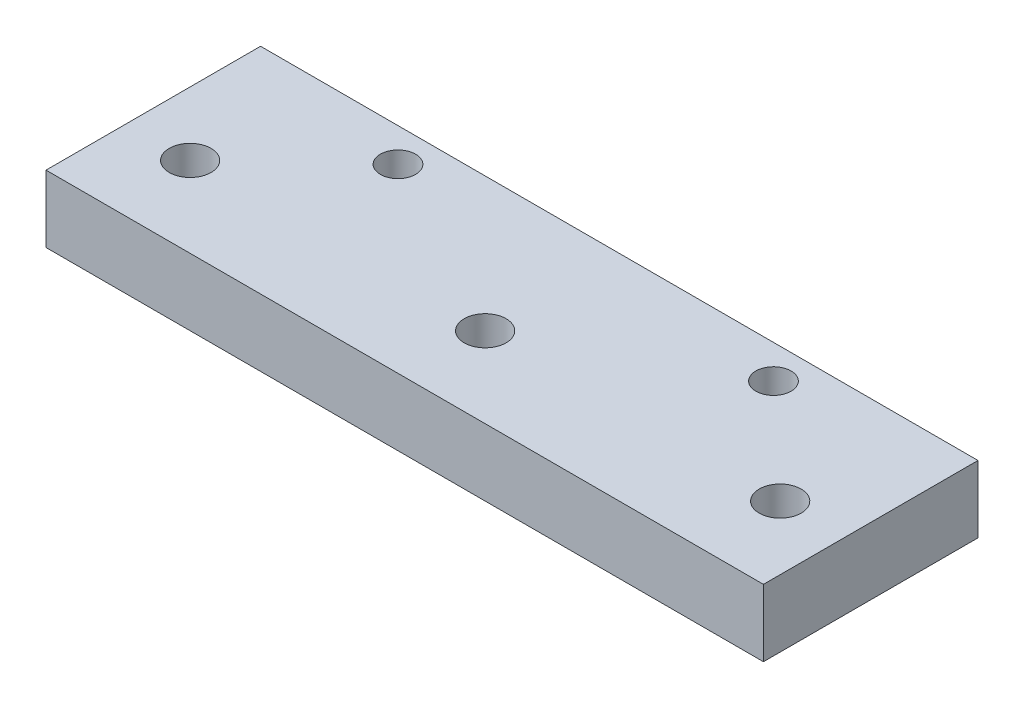
SolidWorks part; units mm, degrees
ref_plane "Front Plane" through (0, 0, 0) normal (0, 0, 1) x (1, 0, 0)
ref_plane "Top Plane" through (0, 0, 0) normal (0, 1, 0) x (1, 0, 0)
ref_plane "Right Plane" through (0, 0, 0) normal (1, 0, 0) x (0, 0, -1)
sketch "Sketch1" plane through (0, 0, 0) normal (0, 1, 0) x (1, 0, 0)
  line L1 (-169.8625, -50.8) -> (169.8625, -50.8)
  line L2 (-169.8625, -50.8) -> (-169.8625, 50.8)
  line L3 (-169.8625, 50.8) -> (169.8625, 50.8)
  line L4 (169.8625, -50.8) -> (169.8625, 50.8)
  line L5 (-169.8625, -50.8) -> (169.8625, 50.8) construction
  line L6 (-169.8625, 50.8) -> (169.8625, -50.8) construction
  point P0 (0, 0)
  dimension "D1" = 169.8625
  dimension "D2" = 50.8
extrude "Boss-Extrude1" add sketch "Sketch1" along normal mid plane 31.75
sketch "Sketch2" plane through (0, 0, 0) normal (0, 1, 0) x (1, 0, 0)
  circle A0 centre (-139.7127, -12.7) radius 9.9187
  circle A1 centre (-0.0127, -12.7) radius 9.9187
  circle A2 centre (139.6873, -12.7) radius 9.9187
  point P6 (0, 0)
  dimension "D1" = 19.8374
  dimension "D2" = 19.8374
  dimension "D3" = 19.8374
  dimension "D4" = 139.7
  dimension "D5" = 279.4
  dimension "D6" = 139.6873
  dimension "D7" = 12.7
extrude "Cut-Extrude2" cut sketch "Sketch2" along normal blind 63.5 from offset 15.875
sketch "Sketch3" plane through (0, 0, 0) normal (0, 1, 0) x (1, 0, 0)
  circle A0 centre (-139.7127, -12.7) radius 15.0876
  circle A1 centre (-0.0127, -12.7) radius 15.0876
  circle A2 centre (139.6873, -12.7) radius 15.0876
  point P6 (0, 0)
  dimension "D1" = 30.1752
  dimension "D2" = 30.1752
  dimension "D3" = 30.1752
  dimension "D4" = 139.7
  dimension "D5" = 279.4
  dimension "D6" = 139.6873
  dimension "D7" = 12.7
extrude "Cut-Extrude4" cut sketch "Sketch3" along normal blind 3.175 from offset 15.875
sketch "Sketch4" plane through (0, 0, 0) normal (0, 1, 0) x (1, 0, 0)
  circle A0 centre (-88.9127, 34.925) radius 8.3312
  circle A1 centre (88.8873, 34.925) radius 8.3312
  point P4 (0, 0)
  dimension "D1" = 16.6624
  dimension "D2" = 16.6624
  dimension "D3" = 177.8
  dimension "D4" = 88.9127
  dimension "D5" = 34.925
extrude "Cut-Extrude6" cut sketch "Sketch4" along normal blind 63.5 from offset 15.875
